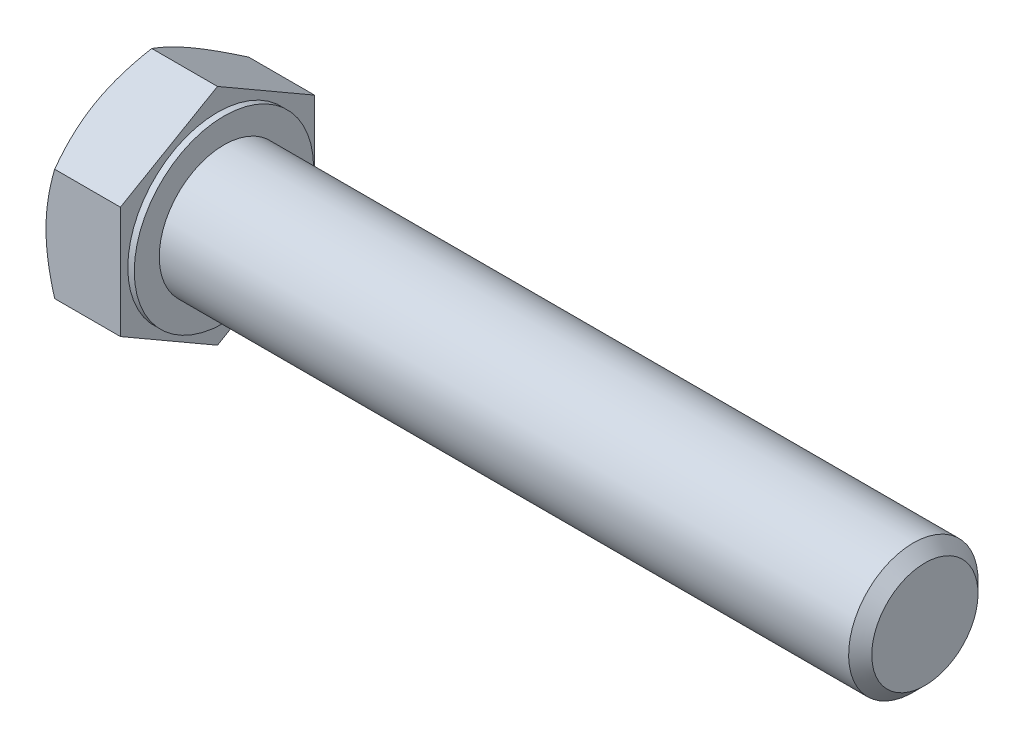
SolidWorks part; units mm, degrees
ref_plane "前基準面" through (0, 0, 0) normal (0, 0, 1) x (1, 0, 0)
ref_plane "上基準面" through (0, 0, 0) normal (0, 1, 0) x (1, 0, 0)
ref_plane "右基準面" through (0, 0, 0) normal (1, 0, 0) x (0, 0, -1)
ref_plane "平面1"
sketch "草圖1" plane through (0, 0, 0) normal (0, 0, 1) x (1, 0, 0)
  line L0 (-0.6001, 0) -> (65, 0)
  line L1 (65, 0) -> (65, 6)
  line L2 (65, 6) -> (35, 6)
  line L3 (35, 6) -> (33.9264, 6)
  line L4 (33.9264, 6) -> (0, 6)
  line L5 (0, 6) -> (0, 8.315)
  line L6 (0, 8.315) -> (-0.6001, 8.315)
  line L7 (-0.6001, 8.315) -> (-0.6001, 0)
  line L8 (65, 0) -> (-0.6001, 0) construction
  dimension "D1" = 65
  dimension "D2" = 90
  dimension "D3" = 6
  dimension "D4" = 0.6001
  dimension "D5" = 90
  dimension "D6" = 1.0736
  dimension "D7" = 6
revolve "本體" add sketch "草圖1" angle 360 about L8
cosmetic thread "裝飾螺紋線1" parameters "D1"=30, "D2"=10.072
sketch "草圖2" plane through (-0.6001, 0, 0) normal (-1, 0, 0) x (0, 0, 1)
  line L0 (0, 10.3923) -> (9, 5.1962)
  line L1 (9, 5.1962) -> (9, -5.1962)
  line L2 (9, -5.1962) -> (0, -10.3923)
  line L3 (0, -10.3923) -> (-9, -5.1962)
  line L4 (-9, -5.1962) -> (-9, 5.1962)
  line L5 (-9, 5.1962) -> (0, 10.3923)
  dimension "D1" = 18
extrude "頭" add sketch "草圖2" along normal blind 6.9
ref_plane "平面2"
sketch "草圖3" plane through (0, 0, 0) normal (0, 0, 1) x (1, 0, 0)
  line L0 (-7.5001, 9) -> (-7.5001, 10.3923)
  line L1 (-7.5001, 10.3923) -> (-6.6963, 10.3923)
  line L2 (-6.6963, 10.3923) -> (-7.5001, 9)
  line L3 (-8.8801, 0) -> (0.7799, 0) construction
  dimension "D1" = 30
  dimension "D2" = 90
revolve "螺紋" cut sketch "草圖3" angle 360 about L3
chamfer "倒角2" distance 1.0735 distance2 1.0736 1 edges at (65, 6, 0)
